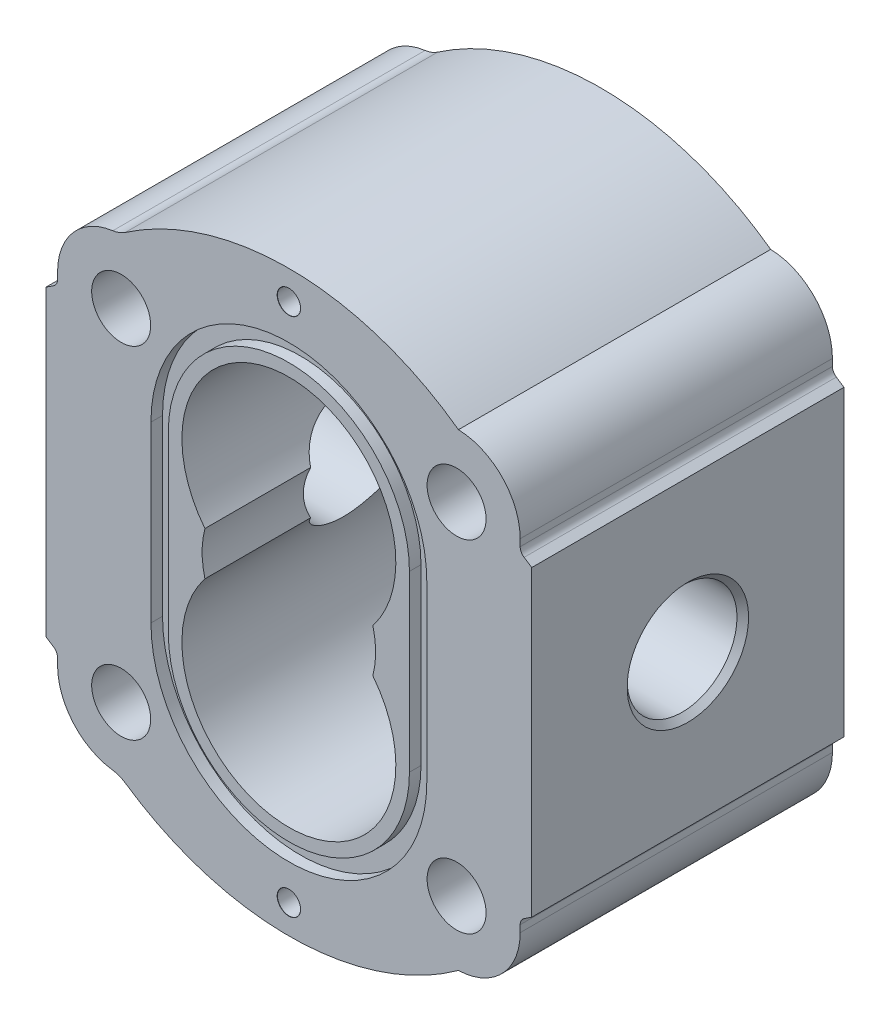
SolidWorks part; units mm, degrees
ref_plane "Ön Düzlem" through (0, 0, 0) normal (0, 0, 1) x (1, 0, 0)
ref_plane "Üst Düzlem" through (0, 0, 0) normal (0, 1, 0) x (1, 0, 0)
ref_plane "Sağ Düzlem" through (0, 0, 0) normal (1, 0, 0) x (0, 0, -1)
sketch "Çizim1" plane through (0, 0, 0) normal (0, 0, 1) x (1, 0, 0)
  line L0 (-112.9139, 0) -> (112.9139, 0) construction
  line L1 (0, 61.4782) -> (0, -61.4782) construction
  line L2 (-40, 29.5) -> (-40, 28.306)
  line L3 (-40.6776, 27.0515) -> (-42, 26.1845)
  line L4 (-42, 26.1845) -> (-42, -26.1845)
  line L5 (40.6776, 27.0515) -> (42, 26.1845)
  line L6 (40, 29.5) -> (40, 28.306)
  line L7 (42, 26.1845) -> (42, -26.1845)
  line L8 (-40.6776, -27.0515) -> (-42, -26.1845)
  line L9 (-40, -29.5) -> (-40, -28.306)
  line L10 (40, -29.5) -> (40, -28.306)
  line L11 (40.6776, -27.0515) -> (42, -26.1845)
  arc A0 (-14.5196, -3.7657) -> (14.5196, -3.7657) centre (0, -15.23) ccw
  arc A1 (14.5196, 3.7657) -> (-14.5196, 3.7657) centre (0, 15.23) ccw
  arc A2 (14.5196, -3.7657) -> (14.5196, 3.7657) centre (0, 0) ccw
  arc A3 (-14.5196, 3.7657) -> (-14.5196, -3.7657) centre (0, 0) ccw
  arc A4 (-28.2748, 41.2375) -> (29.3283, 40.4951) centre (0, 0) cw
  circle A5 centre (-29, 29.5) radius 5.1
  circle A6 centre (29, 29.5) radius 5.1
  arc A7 (-30.4453, 40.4046) -> (-40, 29.5) centre (-29, 29.5) ccw
  arc A8 (29.3283, 40.4951) -> (39.9168, 28.1493) centre (29, 29.5) cw
  arc A9 (-40, 28.306) -> (-40.6776, 27.0515) centre (-41.5, 28.306) cw
  arc A10 (-28.2748, 41.2375) -> (-30.4453, 40.4046) centre (-31.1023, 45.3613) cw
  arc A11 (28.2748, 41.2375) -> (30.4453, 40.4046) centre (31.1023, 45.3613) ccw
  arc A12 (40, 28.306) -> (40.6776, 27.0515) centre (41.5, 28.306) ccw
  arc A13 (30.4453, 40.4046) -> (40, 29.5) centre (29, 29.5) cw
  arc A14 (-28.2748, -41.2375) -> (29.3283, -40.4951) centre (0, 0) ccw
  arc A15 (-28.2748, -41.2375) -> (-30.4453, -40.4046) centre (-31.1023, -45.3613) ccw
  arc A16 (-40, -28.306) -> (-40.6776, -27.0515) centre (-41.5, -28.306) ccw
  arc A17 (-30.4453, -40.4046) -> (-40, -29.5) centre (-29, -29.5) cw
  circle A18 centre (-29, -29.5) radius 5.1
  arc A19 (30.4453, -40.4046) -> (40, -29.5) centre (29, -29.5) ccw
  arc A20 (40, -28.306) -> (40.6776, -27.0515) centre (41.5, -28.306) cw
  arc A21 (28.2748, -41.2375) -> (30.4453, -40.4046) centre (31.1023, -45.3613) cw
  arc A22 (29.3283, -40.4951) -> (39.9168, -28.1493) centre (29, -29.5) ccw
  circle A23 centre (29, -29.5) radius 5.1
  point P13 (0, 0)
  point P16 (0, 0)
  point P24 (-29.3283, -40.4951)
  point P29 (-29.3283, 40.4951)
  point P30 (-40, 29.5)
  point P31 (-42, 0)
  point P32 (0, 0)
  point P33 (-42, 21.3058)
  point P34 (-42, 21.5243)
  point P35 (-40.0693, 28.1062)
  point P36 (-40.9522, 24.5534)
  point P37 (-42, 24.4507)
  point P38 (-40, 27.9721)
  point P39 (0, 0)
  point P40 (-42, 26.1845)
  point P41 (-40, 28.306)
  point P42 (0, 0)
  point P43 (0, 0)
  point P44 (0, 0)
  point P65 (-42, 0)
  point P77 (42, 0)
  dimension "D1" = 37
  dimension "D2" = 37
  dimension "D3" = 30
  dimension "D5" = 10.2
  dimension "D6" = 58
  dimension "D9" = 50
  dimension "D10" = 11
  dimension "D11" = 42
  dimension "D12" = 1.5
  dimension "D13" = 5
  dimension "D4" = 15.23
  dimension "D8" = 29.5
extrude "Yükseklik-Ekstrüzyon1" add sketch "Çizim1" along normal mid plane 54
sketch "Çizim2" plane through (0, 0, 27) normal (0, 0, 1) x (1, 0, 0)
  line L0 (0, -15.04) -> (0, 15.04) construction
  line L1 (23.85, 15.04) -> (23.85, -15.04)
  line L2 (-23.85, 15.04) -> (-23.85, -15.04)
  line L3 (-20.85, 15.04) -> (-20.85, -15.04)
  line L4 (20.85, 15.04) -> (20.85, -15.04)
  arc A0 (23.85, 15.04) -> (-23.85, 15.04) centre (0, 15.04) ccw
  arc A1 (-23.85, -15.04) -> (23.85, -15.04) centre (0, -15.04) ccw
  arc A2 (20.85, 15.04) -> (-20.85, 15.04) centre (0, 15.04) ccw
  arc A3 (-20.85, -15.04) -> (20.85, -15.04) centre (0, -15.04) ccw
  point P4 (0, 0)
  point P5 (0, 0)
  dimension "D2" = 47.7
  dimension "D1" = 15.04
  dimension "D3" = 15.04
  dimension "D4" = 3
extrude "Kes-Ekstrüzyon2" cut sketch "Çizim2" against normal blind 2
mirror "Aynalama1" about plane through (0, 0, 0) normal (0, 0, 1) of "Kes-Ekstrüzyon2"
hole_wizard "G1/2 Dişli Delik1" positions "Çizim4" profile "Çizim5" tap size "G1/2" standard "ISO"
sketch "Çizim4" plane through (42, 0, 0) normal (1, 0, 0) x (0, 0, -1)
  point P0 (0, 0)
sketch "Çizim5" plane through (42, 0, 0) normal (0, 1, 0) x (0, 0, -1)
  line L0 (0, 0) -> (0, 53.0582)
  line L1 (0, 53.0582) -> (9.5, 47.35)
  line L2 (9.5, 47.35) -> (9.5, 1.0025)
  line L3 (9.5, 1.0025) -> (10.5025, 0)
  line L5 (10.5025, 0) -> (0, 0)
  line L6 (-9.5, 1.0025) -> (-10.5025, 0) construction
  line L10 (0, 53.0582) -> (-9.5, 47.35) construction
  line L11 (0, -6.35) -> (0, 107.95) construction
  dimension "Tap Drill Dia." = 19
  dimension "Tap Drill Depth" = 47.35
  dimension "Near C'Sink Dia." = 21.005
  dimension "Near C'Sink Angle" = 90
  dimension "Drill Angle" = 118
cosmetic thread "Delik Dişi1" parameters "D1"=41.91, "D2"=20.955
hole_wizard "G1/2 Dişli Delik2" positions "Çizim8" profile "Çizim9" tap size "G1/2" standard "ISO"
sketch "Çizim8" plane through (-42, 0, 0) normal (-1, 0, 0) x (0, 0, 1)
  point P0 (0, 0)
sketch "Çizim9" plane through (-42, 0, 0) normal (0, 1, 0) x (0, 0, 1)
  line L0 (0, 0) -> (0, 43.0582)
  line L1 (0, 43.0582) -> (9.5, 37.35)
  line L2 (9.5, 37.35) -> (9.5, 1.0025)
  line L3 (9.5, 1.0025) -> (10.5025, 0)
  line L5 (10.5025, 0) -> (0, 0)
  line L6 (-9.5, 1.0025) -> (-10.5025, 0) construction
  line L10 (0, 43.0582) -> (-9.5, 37.35) construction
  line L11 (0, -6.35) -> (0, 107.95) construction
  dimension "Tap Drill Dia." = 19
  dimension "Tap Drill Depth" = 37.35
  dimension "Near C'Sink Dia." = 21.005
  dimension "Near C'Sink Angle" = 90
  dimension "Drill Angle" = 118
cosmetic thread "Delik Dişi2" parameters "D1"=41.91, "D2"=20.955
hole_wizard "Ø4.0 (4) Çap Delik1" positions "Çizim12" profile "Çizim13" hole size "Ø4.0" standard "ISO"
sketch "Çizim12" plane through (0, 0, -27) normal (0, 0, -1) x (-1, 0, 0)
  point P0 (0, 45)
  point P2 (0, -45)
  dimension "D1" = 45
  dimension "D2" = 45
sketch "Çizim13" plane through (0, 45, -27) normal (1, 0, 0) x (0, 1, 0)
  line L0 (0, 0) -> (0, 4.2017)
  line L1 (0, 4.2017) -> (2, 3)
  line L2 (2, 3) -> (2, 0.025)
  line L3 (2, 0.025) -> (2.025, 0)
  line L5 (2.025, 0) -> (0, 0)
  line L6 (-2, 0.025) -> (-2.025, 0) construction
  line L10 (0, 4.2017) -> (-2, 3) construction
  line L11 (0, -6.35) -> (0, 107.95) construction
  dimension "Hole Dia." = 4
  dimension "Hole Depth" = 3
  dimension "Near C'Sink Dia." = 4.05
  dimension "Near C'Sink Angle" = 90
  dimension "Drill Angle" = 118
mirror "Aynalama2" about plane through (0, 0, 0) normal (0, 0, 1) of "Ø4.0 (4) Çap Delik1"
sketch "Çizim14" plane through (-42, 0, 0) normal (-1, 0, 0) x (0, 0, 1)
  text T0 "yusuf berk say"
extrude "Kes-Ekstrüzyon3" cut sketch "Çizim14" against normal blind 2
